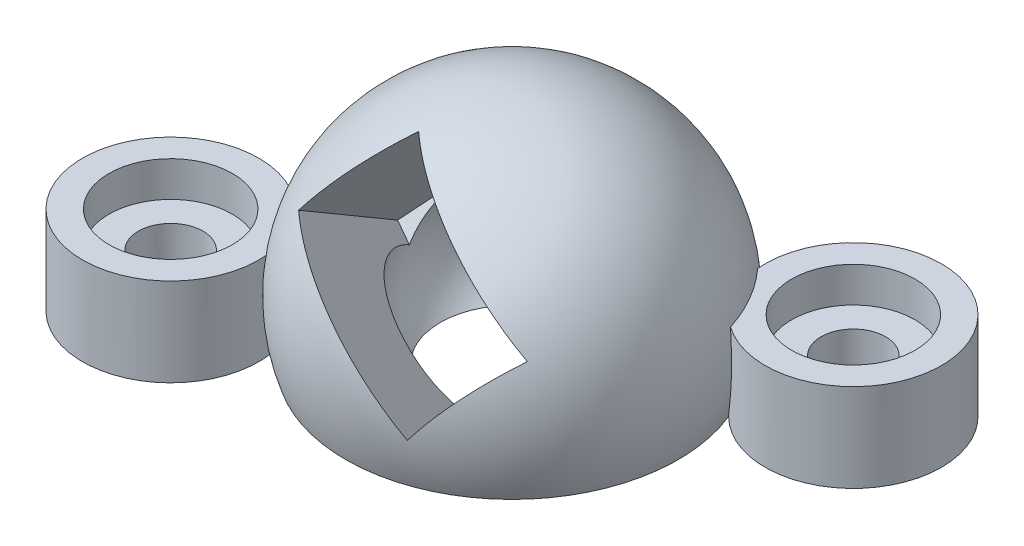
SolidWorks part; units mm, degrees
other "Compression Link 3 Fixed Ball Retainer"
other "Compression Link 3 Fixed Ball Retainer Left"
ref_plane "Front Plane" through (0, 0, 0) normal (0, 0, 1) x (1, 0, 0)
ref_plane "Top Plane" through (0, 0, 0) normal (0, 1, 0) x (1, 0, 0)
ref_plane "Right Plane" through (0, 0, 0) normal (1, 0, 0) x (0, 0, -1)
sketch3d "Retainer Dome axis line"
  line L0 (-71.2917, -83, -25.9808) -> (-71.2917, -63, -25.9808) construction
ref_axis "Retainer Dome axis" through (-71.2917, -83, -25.9808) along (0, 1, 0)
sketch3d "Retainer Dome Section Sketch datum points"
  point P0 (-71.2917, -73, -25.9808)
  point P1 (-76.2917, -73, -34.641)
  point P2 (-71.2917, -63, -25.9808)
ref_plane "Retainer Dome Section Sketch plane" through (-42.2187, 0, 24.375) normal (0.866, 0, -0.5) x (-0.5, 0, -0.866)
sketch "Retainer Dome Section Sketch" plane through (-42.2187, 0, 24.375) normal (0.866, 0, -0.5) x (-0.5, 0, -0.866)
  line L0 (63.8027, -71) -> (58.1458, -71)
  line L1 (58.1458, -71) -> (58.1458, -79)
  arc A0 (58.1458, -79) -> (63.8027, -71) centre (58.1458, -73) ccw
revolve "Retainer Dome" add sketch "Retainer Dome Section Sketch" angle 360 about axis through (-71.2917, -83, -25.9808) along (0, 1, 0)
sketch3d "Retainer Feature 3 profile datum points"
  point P0 (-78.6529, -71, -21.7308)
  point P1 (-68.6529, -71, -21.7308)
  point P2 (-78.6529, -71, -11.7308)
ref_plane "Retainer Feature 3 profile plane" through (0, -71, 0) normal (0, -1, 0) x (-1, 0, 0)
sketch "Retainer Feature 3 profile" plane through (0, -71, 0) normal (0, -1, 0) x (-1, 0, 0)
  circle A0 centre (78.6529, 21.7308) radius 3
extrude "Retainer Feature 3" add sketch "Retainer Feature 3 profile" along normal blind 3
sketch3d "Retainer Feature 4 profile datum points"
  point P0 (-63.9304, -71, -30.2308)
  point P1 (-53.9304, -71, -30.2308)
  point P2 (-63.9304, -71, -20.2308)
ref_plane "Retainer Feature 4 profile plane" through (0, -71, 0) normal (0, -1, 0) x (-1, 0, 0)
sketch "Retainer Feature 4 profile" plane through (0, -71, 0) normal (0, -1, 0) x (-1, 0, 0)
  circle A0 centre (63.9304, 30.2308) radius 3
extrude "Retainer Feature 4" add sketch "Retainer Feature 4 profile" along normal blind 3
sketch3d "Spherical Seat axis line"
  line L0 (-79.9519, -73, -20.9808) -> (-62.6314, -73, -30.9808) construction
ref_axis "Spherical Seat axis" through (-79.9519, -73, -20.9808) along (0.866, 0, -0.5)
sketch3d "Spherical Seat Sketch datum points"
  point P0 (-71.2917, -73, -25.9808)
  point P1 (-76.2917, -73, -34.641)
  point P2 (-62.6314, -73, -30.9808)
ref_plane "Spherical Seat Sketch plane" through (0, -73, 0) normal (0, -1, 0) x (-1, 0, 0)
sketch "Spherical Seat Sketch" plane through (0, -73, 0) normal (0, -1, 0) x (-1, 0, 0)
  line L0 (68.5637, 27.5558) -> (74.0196, 24.4058)
  arc A0 (74.0196, 24.4058) -> (68.5637, 27.5558) centre (71.2917, 25.9808) ccw
revolve "Spherical Seat" cut sketch "Spherical Seat Sketch" angle 360 about axis through (-79.9519, -73, -20.9808) along (0.866, 0, -0.5)
sketch3d "Retainer Feature 6 profile datum points"
  point P0 (-78.6529, -70, -21.7308)
  point P1 (-68.6529, -70, -21.7308)
  point P2 (-78.6529, -70, -11.7308)
ref_plane "Retainer Feature 6 profile plane" through (0, -70, 0) normal (0, -1, 0) x (-1, 0, 0)
sketch "Retainer Feature 6 profile" plane through (0, -70, 0) normal (0, -1, 0) x (-1, 0, 0)
  circle A0 centre (78.6529, 21.7308) radius 1.1
extrude "Retainer Feature 6" cut sketch "Retainer Feature 6 profile" along normal blind 4.25
sketch3d "Retainer Feature 7 profile datum points"
  point P0 (-78.6529, -72.8, -21.7308)
  point P1 (-68.6529, -72.8, -21.7308)
  point P2 (-78.6529, -72.8, -11.7308)
ref_plane "Retainer Feature 7 profile plane" through (0, -72.8, 0) normal (0, -1, 0) x (-1, 0, 0)
sketch "Retainer Feature 7 profile" plane through (0, -72.8, 0) normal (0, -1, 0) x (-1, 0, 0)
  circle A0 centre (78.6529, 21.7308) radius 2.1
extrude "Retainer Feature 7" cut sketch "Retainer Feature 7 profile" along normal blind 1.45
sketch3d "Retainer Feature 8 profile datum points"
  point P0 (-63.9304, -70, -30.2308)
  point P1 (-53.9304, -70, -30.2308)
  point P2 (-63.9304, -70, -20.2308)
ref_plane "Retainer Feature 8 profile plane" through (0, -70, 0) normal (0, -1, 0) x (-1, 0, 0)
sketch "Retainer Feature 8 profile" plane through (0, -70, 0) normal (0, -1, 0) x (-1, 0, 0)
  circle A0 centre (63.9304, 30.2308) radius 1.1
extrude "Retainer Feature 8" cut sketch "Retainer Feature 8 profile" along normal blind 4.25
sketch3d "Retainer Feature 9 profile datum points"
  point P0 (-63.9304, -72.8, -30.2308)
  point P1 (-53.9304, -72.8, -30.2308)
  point P2 (-63.9304, -72.8, -20.2308)
ref_plane "Retainer Feature 9 profile plane" through (0, -72.8, 0) normal (0, -1, 0) x (-1, 0, 0)
sketch "Retainer Feature 9 profile" plane through (0, -72.8, 0) normal (0, -1, 0) x (-1, 0, 0)
  circle A0 centre (63.9304, 30.2308) radius 2.1
extrude "Retainer Feature 9" cut sketch "Retainer Feature 9 profile" along normal blind 1.45
sketch3d "Middle Right Fixed Compression Ball Retainer 1 Angular Clearance Sketch 21 datum points"
  point P0 (-71.2917, -73, -25.9808)
  point P1 (-79.3909, -78.3859, -28.3032)
  point P2 (-65.5478, -79.4818, -30.9801)
ref_plane "Middle Right Fixed Compression Ball Retainer 1 Angular Clearance Sketch 21 plane" through (1.087, -4.9285, 7.6389) normal (0.1187, -0.5383, 0.8343) x (0.9929, 0.0644, -0.0998)
sketch "Middle Right Fixed Compression Ball Retainer 1 Angular Clearance Sketch 21" plane through (1.087, -4.9285, 7.6389) normal (0.1187, -0.5383, 0.8343) x (0.9929, 0.0644, -0.0998)
  line L0 (-71.3831, -72.0252) -> (-76.6036, -75.7275)
  line L1 (-76.6036, -75.7275) -> (-74.4053, -78.8271)
  line L2 (-74.4053, -78.8271) -> (-69.1849, -75.1249)
  line L3 (-69.1849, -75.1249) -> (-71.3831, -72.0252)
extrude "Retainer Feature 12" cut sketch "Middle Right Fixed Compression Ball Retainer 1 Angular Clearance Sketch 21" along normal blind 10
sketch3d "Mirror1 profile datum points"
  point P0 (0, 0, 0)
  point P1 (10, 0, 0)
  point P2 (0, 0, 10)
ref_plane "Mirror1 profile plane" through (0, 0, 0) normal (0, -1, 0) x (-1, 0, 0)
mirror "Mirror1" about plane through (0, 0, 0) normal (0, -1, 0) of bodies 109
delete or keep bodies "Remove1" type delete bodies bodies 109
